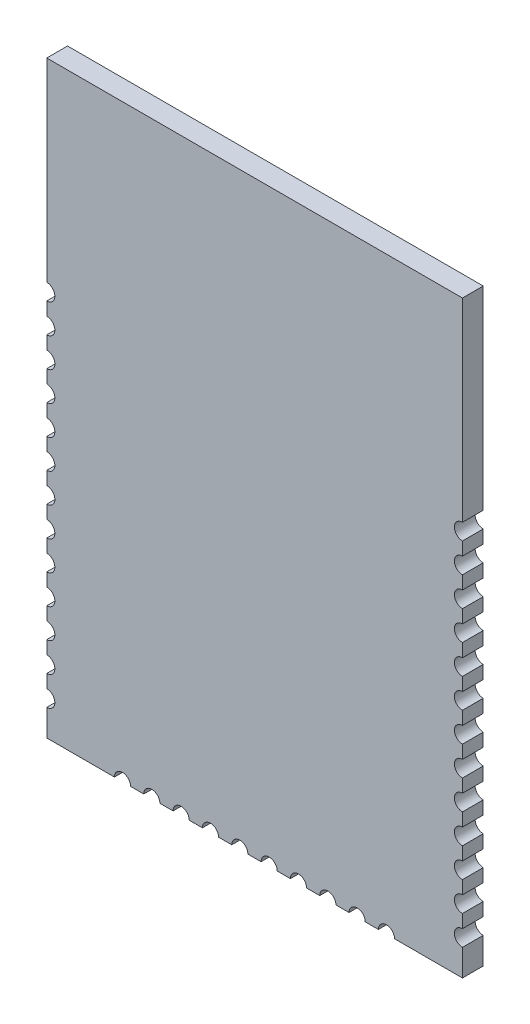
SolidWorks part; units mm, degrees
ref_plane "Plano frontal" through (0, 0, 0) normal (0, 0, 1) x (1, 0, 0)
ref_plane "Plano superior" through (0, 0, 0) normal (0, 1, 0) x (1, 0, 0)
ref_plane "Plano direito" through (0, 0, 0) normal (1, 0, 0) x (0, 0, -1)
sketch "Esboço1" plane through (0, 0, 0) normal (0, 0, 1) x (1, 0, 0)
  line L1 (9, -12.75) -> (-9, -12.75)
  line L2 (9, -12.75) -> (9, 12.75)
  line L3 (9, 12.75) -> (-9, 12.75)
  line L4 (-9, -12.75) -> (-9, 12.75)
  line L5 (9, -12.75) -> (-9, 12.75) construction
  line L6 (9, 12.75) -> (-9, -12.75) construction
  point P0 (0, 0)
  dimension "D1" = 18
  dimension "D2" = 25.5
extrude "Ressalto-extrusão1" add sketch "Esboço1" along normal mid plane 0.9
sketch "Esboço2" plane through (0, 0, 0.45) normal (0, 0, 1) x (1, 0, 0)
  line L0 (-9, -12.75) -> (9, -12.75) construction
  line L1 (-9, 12.75) -> (-9, -12.75) construction
  circle A0 centre (-5.72, -12.75) radius 0.35
  circle A1 centre (-4.45, -12.75) radius 0.35
  circle A2 centre (-3.18, -12.75) radius 0.35
  circle A3 centre (-1.91, -12.75) radius 0.35
  circle A4 centre (-0.64, -12.75) radius 0.35
  circle A5 centre (0.63, -12.75) radius 0.35
  circle A6 centre (1.9, -12.75) radius 0.35
  circle A7 centre (3.17, -12.75) radius 0.35
  circle A8 centre (4.44, -12.75) radius 0.35
  circle A9 centre (5.71, -12.75) radius 0.35
  dimension "D2" = 0.7
  dimension "D1" = 3.28
  dimension "D4" = 4.55
  dimension "D6" = 18
  dimension "D3" = 10
extrude "Corte-extrusão1" cut sketch "Esboço2" against normal through all
sketch "Esboço3" plane through (0, 0, 0.45) normal (0, 0, 1) x (1, 0, 0)
  line L0 (-9, 12.75) -> (-9, -12.75) construction
  line L1 (-9, -12.75) -> (-6.07, -12.75) construction
  line L2 (-5.37, -12.75) -> (-4.8, -12.75) construction
  line L3 (0, -55) -> (0, 55) construction
  circle A0 centre (-9, -11.25) radius 0.35
  circle A1 centre (-9, -9.98) radius 0.35
  circle A2 centre (-9, -8.71) radius 0.35
  circle A3 centre (-9, -7.44) radius 0.35
  circle A4 centre (-9, -6.17) radius 0.35
  circle A5 centre (-9, -4.9) radius 0.35
  circle A6 centre (-9, -3.63) radius 0.35
  circle A7 centre (-9, -2.36) radius 0.35
  circle A8 centre (-9, -1.09) radius 0.35
  circle A9 centre (-9, 0.18) radius 0.35
  circle A10 centre (-9, 1.45) radius 0.35
  circle A11 centre (-9, 2.72) radius 0.35
  circle A12 centre (-9, 3.99) radius 0.35
  circle A15 centre (9, 3.99) radius 0.35
  circle A16 centre (9, 2.72) radius 0.35
  circle A17 centre (9, 1.45) radius 0.35
  circle A18 centre (9, 0.18) radius 0.35
  circle A19 centre (9, -1.09) radius 0.35
  circle A20 centre (9, -2.36) radius 0.35
  circle A21 centre (9, -3.63) radius 0.35
  circle A22 centre (9, -4.9) radius 0.35
  circle A23 centre (9, -6.17) radius 0.35
  circle A24 centre (9, -7.44) radius 0.35
  circle A25 centre (9, -8.71) radius 0.35
  circle A26 centre (9, -9.98) radius 0.35
  circle A27 centre (9, -11.25) radius 0.35
  circle A28 centre (-9, 5.26) radius 0.35 [skipped]
  dimension "D1" = 0.7
  dimension "D2" = 1.5
  dimension "D4" = 6.35
  dimension "D5" = 2.77
  dimension "D3" = 14
extrude "Corte-extrusão2" cut sketch "Esboço3" against normal through all
